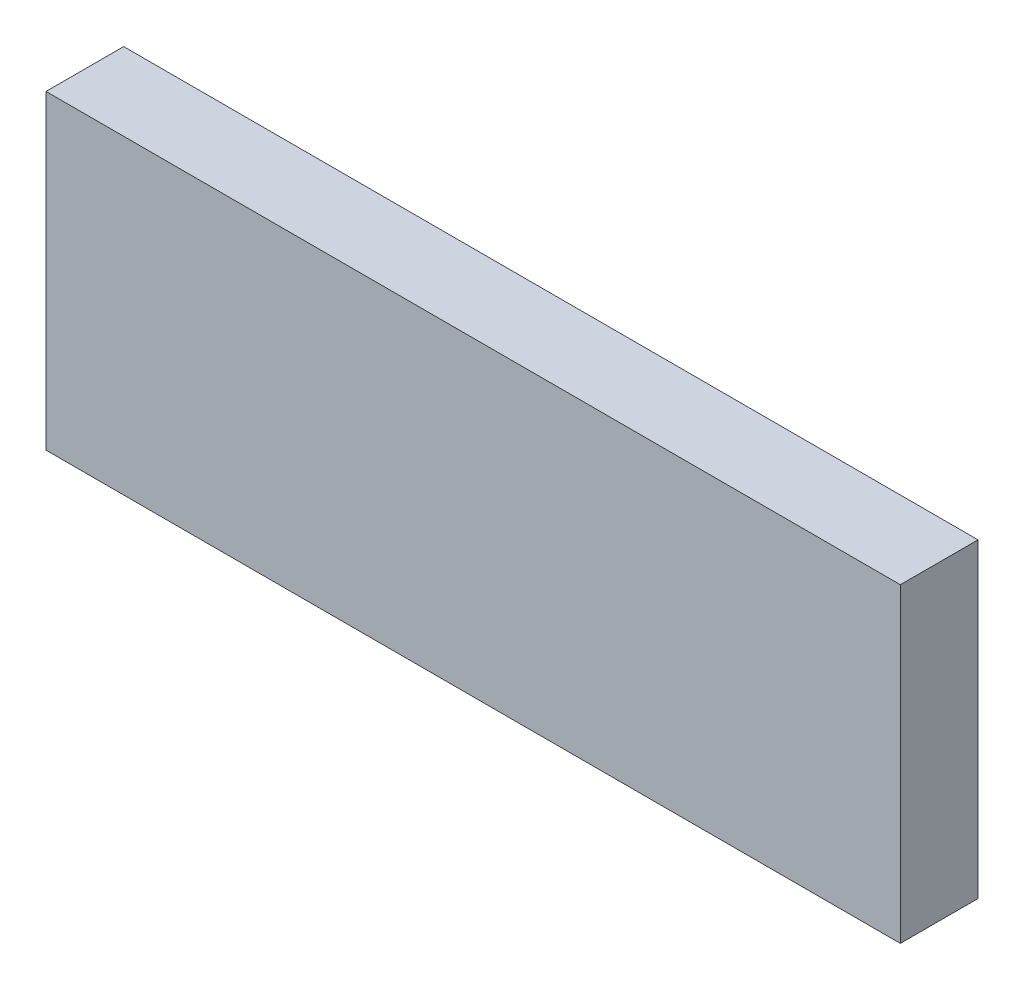
SolidWorks part; units mm, degrees
ref_plane "Front Plane" through (0, 0, 0) normal (0, 0, 1) x (1, 0, 0)
ref_plane "Top Plane" through (0, 0, 0) normal (0, 1, 0) x (1, 0, 0)
ref_plane "Right Plane" through (0, 0, 0) normal (1, 0, 0) x (0, 0, -1)
sketch "Sketch2" plane through (0, 0, 0) normal (0, 0, 1) x (1, 0, 0)
  line L1 (-46.0306, 34.925) -> (23.8194, 34.925)
  line L2 (-46.0306, 34.925) -> (-46.0306, 9.525)
  line L3 (-46.0306, 9.525) -> (23.8194, 9.525)
  line L4 (23.8194, 34.925) -> (23.8194, 9.525)
extrude "Boss-Extrude1" add sketch "Sketch2" along normal blind 6.35
sketch "Sketch3" plane through (0, 0, 6.35) normal (0, 0, 1) x (1, 0, 0)
  line L0 (-46.0306, 22.225) -> (23.8194, 22.225) construction
  line L1 (-46.0306, 34.925) -> (-46.0306, 9.525) construction
  line L2 (23.8194, 9.525) -> (23.8194, 34.925) construction
  line L3 (-11.1056, 34.925) -> (-11.1056, 9.525) construction
  line L4 (23.8194, 34.925) -> (-46.0306, 34.925) construction
  line L5 (-46.0306, 9.525) -> (23.8194, 9.525) construction
  circle A0 centre (-33.3306, 22.225) radius 6.35
  circle A1 centre (11.1194, 22.225) radius 6.35
  dimension "D1" = 44.45
  dimension "D3" = 12.7
  dimension "D2" = 22.225
equation "\"Height@Sketch2\"= ( 4 / 11 ) * \"Length@Sketch2\""
equation "\"Depth@Boss-Extrude1\"= ( 1 / 11 ) * \"Length@Sketch2\""
